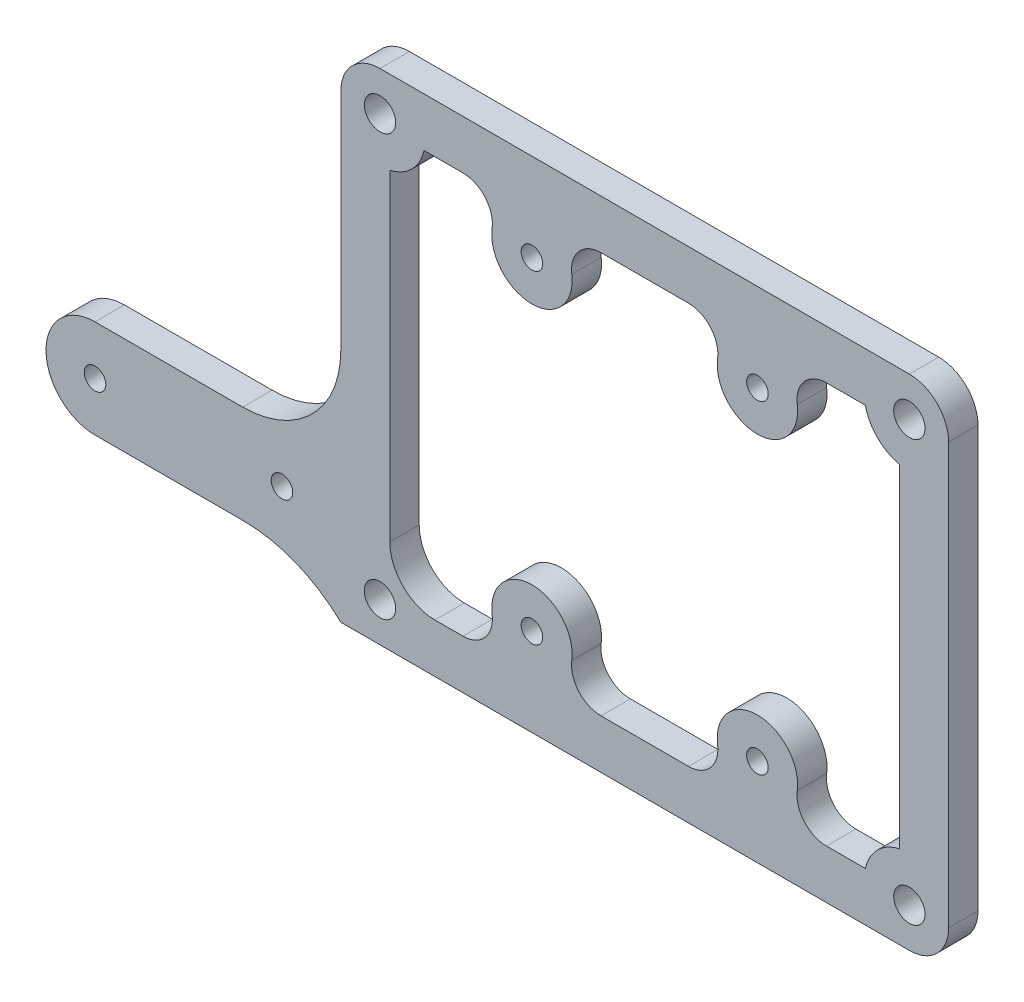
SolidWorks part; units mm, degrees
ref_plane "前视基准面" through (0, 0, 0) normal (0, 0, 1) x (1, 0, 0)
ref_plane "上视基准面" through (0, 0, 0) normal (0, 1, 0) x (1, 0, 0)
ref_plane "右视基准面" through (0, 0, 0) normal (1, 0, 0) x (0, 0, -1)
sketch "草图1" plane through (0, 0, 0) normal (0, 0, 1) x (1, 0, 0)
  line L0 (0, 0) -> (19.2937, 0) construction
  line L1 (0, 0) -> (0, 25.0119) construction
  line L2 (-26, 20.46) -> (-26, 20.211)
  line L7 (-31, 25.46) -> (31, 25.46)
  line L8 (-31, 25.46) -> (-31, -1.46)
  line L9 (-31, -25.46) -> (31, -25.46)
  line L10 (31, 25.46) -> (31, -25.46)
  line L12 (26, 20.46) -> (26, 20.211)
  line L13 (-26, 20.46) -> (-25.751, 20.46)
  line L14 (-22.51, 20.46) -> (-18.5348, 20.46)
  line L15 (-26, 20.46) -> (26, 20.46) construction
  line L16 (-26, 16.97) -> (-26, -15.86)
  line L17 (-26, 20.46) -> (-26, -20.46) construction
  line L18 (25.751, 20.46) -> (26, 20.46)
  line L19 (26, 16.97) -> (26, -16.97)
  line L20 (26, 20.46) -> (26, -20.46) construction
  line L21 (26, -20.211) -> (26, -20.46)
  line L22 (25.751, -20.46) -> (26, -20.46)
  line L23 (-26, -20.46) -> (26, -20.46) construction
  line L25 (-21.4, -20.46) -> (-18.5348, -20.46)
  line L26 (-4.4652, -20.46) -> (4.4652, -20.46)
  line L27 (18.5348, -20.46) -> (22.51, -20.46)
  line L28 (-4.4652, 20.46) -> (4.4652, 20.46)
  line L29 (18.5348, 20.46) -> (22.51, 20.46)
  line L30 (-56.07, -16.46) -> (-37, -16.46) construction
  line L31 (-56.07, -11.46) -> (-41, -11.46)
  line L32 (-56.07, -21.46) -> (-41, -21.46)
  line L35 (-31, 25.46) -> (-31, -25.46) construction
  circle A0 centre (-27, 21.46) radius 1.6
  circle A1 centre (27, 21.46) radius 1.6
  circle A2 centre (-27, -21.46) radius 1.6
  circle A3 centre (27, -21.46) radius 1.6
  circle A4 centre (-11.5, 16.5) radius 1.1
  circle A5 centre (11.5, 16.5) radius 1.1
  circle A6 centre (11.5, -16.5) radius 1.1
  circle A7 centre (-11.5, -16.5) radius 1.1
  arc A8 (-26, 16.97) -> (-22.51, 20.46) centre (-27, 21.46) ccw
  arc A10 (26, -16.97) -> (22.51, -20.46) centre (27, -21.46) ccw
  arc A11 (22.51, 20.46) -> (26, 16.97) centre (27, 21.46) ccw
  arc A12 (7.4377, 17.0544) -> (15.5623, 17.0544) centre (11.5, 16.5) ccw
  arc A13 (-15.5623, 17.0544) -> (-7.4377, 17.0544) centre (-11.5, 16.5) ccw
  arc A14 (-7.4377, -17.0544) -> (-15.5623, -17.0544) centre (-11.5, -16.5) ccw
  arc A15 (15.5623, -17.0544) -> (7.4377, -17.0544) centre (11.5, -16.5) ccw
  circle A16 centre (-27, 21.46) radius 4.6 construction
  circle A17 centre (27, 21.46) radius 4.6 construction
  circle A18 centre (-56.07, -16.46) radius 1.1
  circle A19 centre (27, -21.46) radius 4.6 construction
  circle A20 centre (-37, -16.46) radius 1.1
  arc A21 (-56.07, -11.46) -> (-56.07, -21.46) centre (-56.07, -16.46) ccw
  circle A23 centre (-11.5, -16.5) radius 4.1 construction
  circle A24 centre (11.5, -16.5) radius 4.1 construction
  circle A25 centre (-11.5, 16.5) radius 4.1 construction
  circle A26 centre (11.5, 16.5) radius 4.1 construction
  arc A27 (18.5348, -20.46) -> (15.5623, -17.0544) centre (18.5348, -17.46) cw
  arc A28 (4.4652, -20.46) -> (7.4377, -17.0544) centre (4.4652, -17.46) ccw
  arc A29 (-4.4652, -20.46) -> (-7.4377, -17.0544) centre (-4.4652, -17.46) cw
  arc A30 (-18.5348, -20.46) -> (-15.5623, -17.0544) centre (-18.5348, -17.46) ccw
  arc A31 (18.5348, 20.46) -> (15.5623, 17.0544) centre (18.5348, 17.46) ccw
  arc A32 (4.4652, 20.46) -> (7.4377, 17.0544) centre (4.4652, 17.46) cw
  arc A33 (-18.5348, 20.46) -> (-15.5623, 17.0544) centre (-18.5348, 17.46) cw
  arc A34 (-4.4652, 20.46) -> (-7.4377, 17.0544) centre (-4.4652, 17.46) ccw
  arc A35 (-31, -1.46) -> (-41, -11.46) centre (-41, -1.46) cw
  arc A36 (-41, -21.46) -> (-31, -25.46) centre (-41, -35.96) cw
  arc A37 (-21.4, -20.46) -> (-26, -15.86) centre (-21.4, -15.86) cw
  point P61 (-44.535, -16.46)
  point P85 (12.5623, 20.46)
  point P92 (-10.4377, 20.46)
  dimension "D3" = 3.2
  dimension "D6" = 2.2
  dimension "D4" = 4
  dimension "D13" = 3
  dimension "D14" = 19.07
  dimension "D15" = 2.2
  dimension "D16" = 2.2
  dimension "D19" = 5
  dimension "D20" = 10
  dimension "D21" = 4.6
  dimension "D1" = 54
  dimension "D2" = 42.92
  dimension "D5" = 4
  dimension "D7" = 23
  dimension "D8" = 23
  dimension "D9" = 16.5
  dimension "D10" = 16.5
  dimension "D17" = 10
  dimension "D18" = 5
  dimension "D22" = 40.92
  dimension "D11" = 5
  dimension "D12" = 3
extrude "凸台-拉伸1" add sketch "草图1" along normal blind 3
fillet "圆角2" radius 4 3 edges at (31, 25.46, 1.5) (31, -25.46, 1.5) (-31, 25.46, 1.5)
